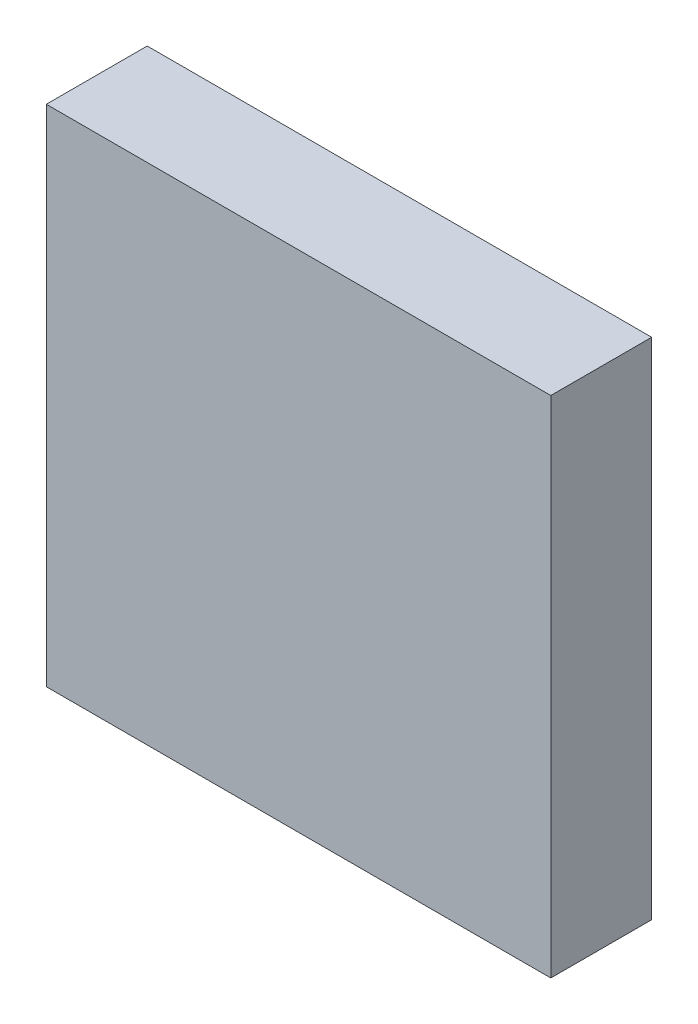
SolidWorks part; units mm, degrees
ref_plane "Спереди" through (0, 0, 0) normal (0, 0, 1) x (1, 0, 0)
ref_plane "Сверху" through (0, 0, 0) normal (0, 1, 0) x (1, 0, 0)
ref_plane "Справа" through (0, 0, 0) normal (1, 0, 0) x (0, 0, -1)
sketch "Эскиз1" plane through (0, 0, 0) normal (0, 0, 1) x (1, 0, 0)
  line L1 (-20, 0) -> (0, 0)
  line L2 (-20, 0) -> (-20, -20)
  line L3 (-20, -20) -> (0, -20)
  line L4 (0, 0) -> (0, -20)
  point P4 (0, 0)
  point P5 (0, 0)
  point P7 (0, 0)
  dimension "D1" = 20
extrude "Бобышка-Вытянуть1" add sketch "Эскиз1" along normal blind 4
